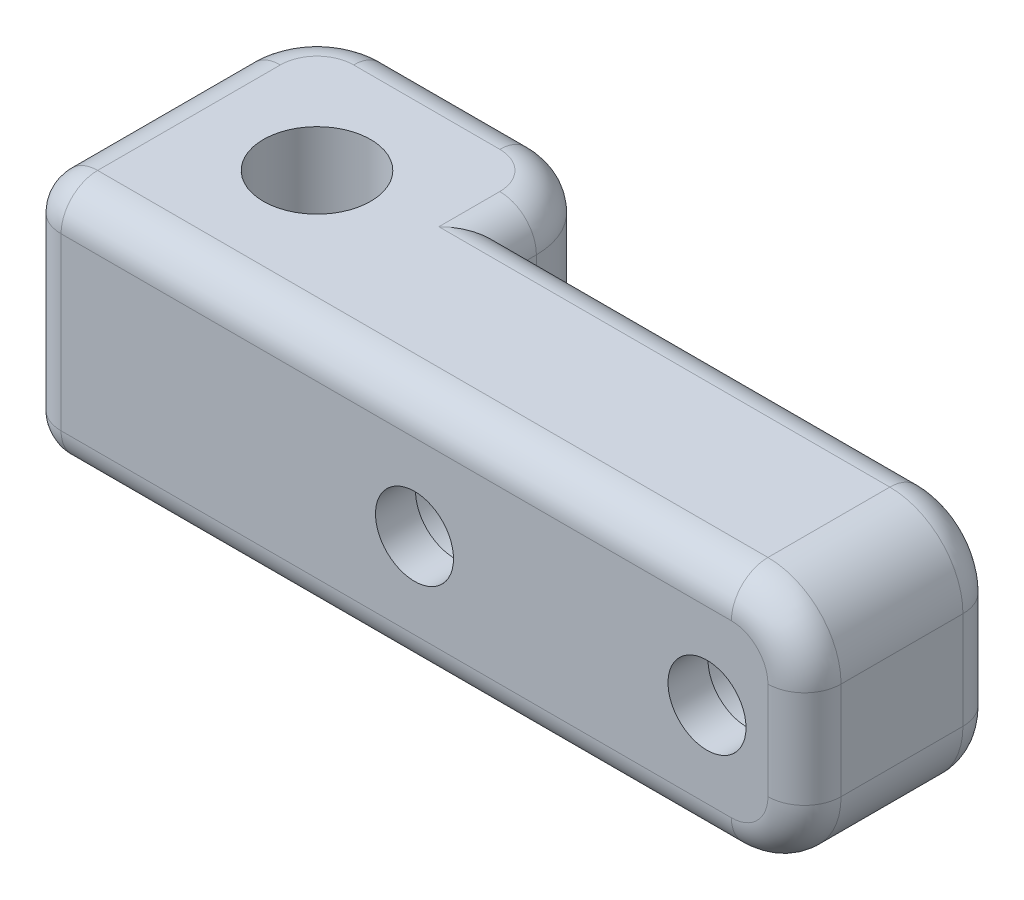
SolidWorks part; units mm, degrees
ref_plane "Front Plane" through (0, 0, 0) normal (0, 0, 1) x (1, 0, 0)
ref_plane "Top Plane" through (0, 0, 0) normal (0, 1, 0) x (1, 0, 0)
ref_plane "Right Plane" through (0, 0, 0) normal (1, 0, 0) x (0, 0, -1)
sketch "Sketch1" plane through (0, 0, 0) normal (0, 1, 0) x (1, 0, 0)
  line L1 (0, 0) -> (12, 0)
  line L2 (0, 0) -> (0, 12)
  line L3 (0, 12) -> (12, 12)
  line L4 (12, 0) -> (12, 12)
  dimension "D1" = 12
  dimension "D2" = 12
extrude "Boss-Extrude1" add sketch "Sketch1" along normal blind 10
sketch "Sketch2" plane through (0, 10, 0) normal (0, 1, 0) x (1, 0, 0)
  line L0 (12, 12) -> (0, 12) construction
  line L1 (0, 12) -> (0, 0) construction
  circle A0 centre (6, 6) radius 1.5
  point P0 (6, 6)
  dimension "D1" = 3
  dimension "D2" = 6
  dimension "D3" = 6
sketch "Sketch3" plane through (12, 0, 0) normal (1, 0, 0) x (0, 0, -1)
  line L0 (0, 0) -> (12, 0) construction
  line L1 (0, 10) -> (8, 10)
  line L2 (0, 10) -> (0, 0)
  line L3 (0, 0) -> (8, 0)
  line L4 (8, 10) -> (8, 0)
  dimension "D1" = 8
extrude "Boss-Extrude3" add sketch "Sketch3" along normal blind 20
sketch "Sketch4" plane through (0, 0, 0) normal (0, 0, 1) x (1, 0, 0)
  line L0 (22, 10) -> (22, 0) construction
  line L3 (16, 5) -> (28, 5) construction
  line L6 (0, 10) -> (0, 0) construction
  point P7 (28, 5)
  point P8 (16, 5)
  point P9 (22, 5)
  dimension "D1" = 12
  dimension "D2" = 16
hole_wizard "M3 Clearance Hole1" positions "Sketch4" profile "Sketch5" hole size "M3" standard "ANSI Metric"
sketch "Sketch5" plane through (16, 5, 0) normal (1, 0, 0) x (0, -1, 0)
  line L0 (0, 0) -> (0, 12)
  line L1 (0, 12) -> (1.6, 12)
  line L2 (1.6, 12) -> (1.6, 0)
  line L5 (1.6, 0) -> (0, 0)
  line L11 (0, -6.35) -> (0, 107.95) construction
  dimension "Thru Hole Dia." = 3.2
  dimension "Thru Hole Depth" = 12
fillet "Fillet3" radius 3 4 edges at (32, 0, -4) (32, 10, -4) (0, 5, -12) (12, 5, -12)
sketch "Sketch6" plane through (0, 0, -8) normal (0, 0, -1) x (-1, 0, 0)
  point P0 (-28, 5)
  point P1 (-16, 5)
hole_wizard "Ø4.4 (4.4) Diameter Hole1" positions "Sketch6" profile "Sketch7" hole size "Ø4.4" standard "ANSI Metric"
sketch "Sketch7" plane through (28, 5, -8) normal (1, 0, 0) x (0, 1, 0)
  line L0 (0, 0) -> (0, 7.3219)
  line L1 (0, 7.3219) -> (2.2, 6)
  line L2 (2.2, 6) -> (2.2, 0)
  line L5 (2.2, 0) -> (0, 0)
  line L10 (0, 7.3219) -> (-2.2, 6) construction
  line L11 (0, -6.35) -> (0, 107.95) construction
  dimension "Hole Dia." = 4.4
  dimension "Hole Depth" = 6
  dimension "Drill Angle" = 118
fillet "Fillet4" radius 1.5 21 edges at (12, 0, -8.5) (11.1213, 0, -11.1213) (6, 0, -12) (0.8787, 0, -11.1213) (20.5, 0, -8) (31.1213, 0.8787, -8) (32, 5, -8) (31.1213, 9.1213, -8) (12, 10, -8.5) (11.1213, 10, -11.1213) (6, 10, -12) (0.8787, 10, -11.1213) (14.5, 0, 0) (31.1213, 0.8787, 0) (32, 5, 0) (31.1213, 9.1213, 0) (0, 0, -4.5) (20.5, 10, -8) (0, 10, -4.5) (14.5, 10, 0) (0, 5, 0)
hole_wizard "Hole1" positions "Sketch2" profile "Sketch8" legacy
sketch "Sketch8" plane through (6, 10, -6) normal (1, 0, 0) x (0, 0, 1)
  line L0 (0, 0) -> (0, 100)
  line L1 (0, 100) -> (1.6, 100)
  line L2 (1.6, 100) -> (1.6, 6)
  line L3 (1.6, 6) -> (2.2, 6)
  line L4 (2.2, 6) -> (2.2, 0)
  line L5 (2.2, 0) -> (0, 0)
  line L6 (0, 110) -> (0, -10) construction
  dimension "Diameter" = 3.2
  dimension "Depth" = 100
  dimension "C-Bore Diameter" = 4.4
  dimension "C-Bore Depth" = 6
